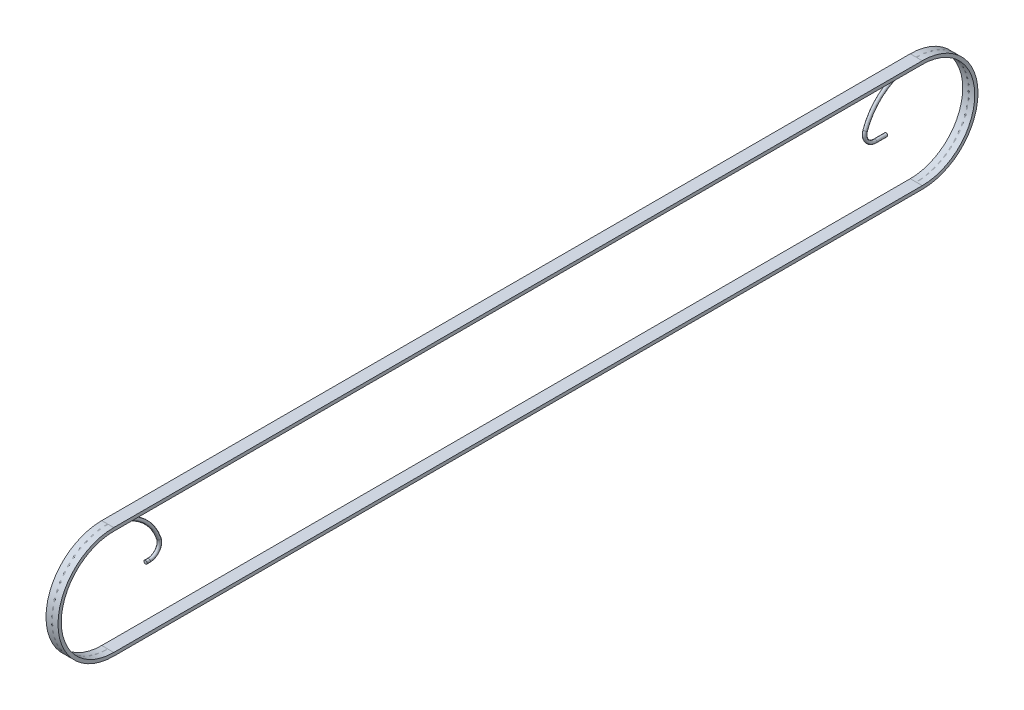
SolidWorks part; units mm, degrees
material "6061-T6 (SS)"
ref_plane "Front Plane" through (0, 0, 0) normal (0, 0, 1) x (1, 0, 0)
ref_plane "Top Plane" through (0, 0, 0) normal (0, 1, 0) x (1, 0, 0)
ref_plane "Right Plane" through (0, 0, 0) normal (1, 0, 0) x (0, 0, -1)
sketch "Sketch1" plane through (0, 0, 0) normal (1, 0, 0) x (0, 0, -1)
  line L0 (0, 80.9625) -> (1174.6682, 80.9625)
  line L2 (1174.6682, 76.2) -> (0, 76.2)
  line L3 (0, -80.9625) -> (1174.6682, -80.9625)
  line L5 (1174.6682, -76.2) -> (0, -76.2)
  arc A0 (0, 80.9625) -> (0, -80.9625) centre (0, 0) ccw
  arc A1 (0, 76.2) -> (0, -76.2) centre (0, 0) ccw
  arc A2 (1174.6682, -76.2) -> (1174.6682, 76.2) centre (1174.6682, 0) ccw
  arc A3 (1174.6682, 80.9625) -> (1174.6682, -80.9625) centre (1174.6682, 0) cw
  circle A4 centre (1174.6682, 0) radius 76.2 construction
  circle A5 centre (0, 0) radius 76.2 construction
  dimension "D1" = 152.4
  dimension "D2" = 4.7625
  dimension "D3" = 1174.6682
extrude "Boss-Extrude1" add sketch "Sketch1" along normal mid plane 17.4625
sketch "Sketch2" plane through (0, 0, 0) normal (1, 0, 0) x (0, 0, -1)
  line L0 (59.6063, 7.9375) -> (59.6063, -7.9375) construction
  line L1 (0, 76.2) -> (0, 80.9625) construction
  line L2 (1115.0619, 7.9375) -> (1115.0619, -7.9375) construction
  line L3 (0, -78.5813) -> (1174.6682, -78.5813)
  line L4 (1115.0619, 5.5562) -> (1130.8734, 5.5562)
  line L5 (59.6063, 5.5562) -> (54.8438, 5.5562)
  line L6 (1128.5239, 13.8933) -> (1128.5239, -14.2626) construction
  line L7 (1136.7789, 13.8933) -> (1136.7789, -14.2626) construction
  arc A0 (74.1335, 26.0621) -> (0, -78.5813) centre (0, 0) ccw
  arc A1 (71.887, 25.2724) -> (59.6063, 7.9375) centre (59.6063, 20.955) cw construction
  arc A2 (0, 76.2) -> (0, -76.2) centre (0, 0) ccw construction
  arc A3 (59.6063, 5.5562) -> (74.1335, 26.0621) centre (59.6063, 20.955) ccw
  arc A4 (1174.6682, -78.5813) -> (1100.5347, 26.0621) centre (1174.6682, 0) ccw
  arc A5 (1174.6682, -76.2) -> (1174.6682, 76.2) centre (1174.6682, 0) ccw construction
  arc A6 (1100.5347, 26.0621) -> (1115.0619, 5.5562) centre (1115.0619, 20.955) ccw
  point P10 (59.6063, 0)
  point P18 (0, 78.5813)
  point P27 (1115.0619, 0)
  dimension "D1" = 26.035
  dimension "D3" = 8.255
  dimension "D8" = 1941.5106
  dimension "D2" = 15.875
  dimension "D4" = 4.7625
  dimension "D5" = 13.462
  dimension "D6" = 2.3495
  dimension "D7" = 5.9055
sweep "Sweep1" add path "Sketch2" circular profile diameter 4.7625 parameters "D3"=4.7625
